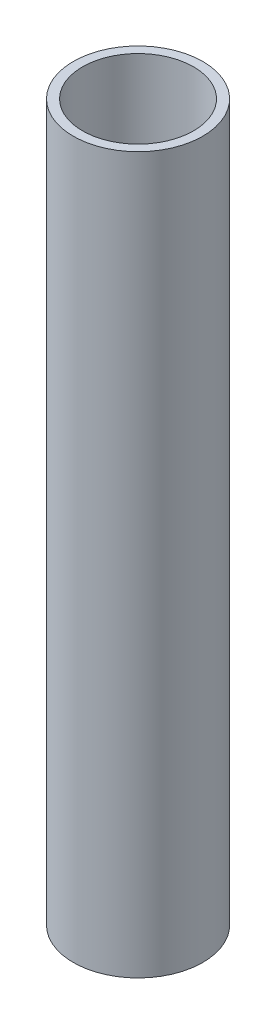
SolidWorks part; units mm, degrees
ref_plane "Front Plane" through (0, 0, 0) normal (0, 0, 1) x (1, 0, 0)
ref_plane "Top Plane" through (0, 0, 0) normal (0, 1, 0) x (1, 0, 0)
ref_plane "Right Plane" through (0, 0, 0) normal (1, 0, 0) x (0, 0, -1)
sketch "Sketch1" plane through (0, 0, 0) normal (0, 1, 0) x (1, 0, 0)
  circle A0 centre (0, 0) radius 18
  circle A1 centre (0, 0) radius 21
extrude "Boss-Extrude1" add sketch "Sketch1" along normal blind 232 contours A1 A0
